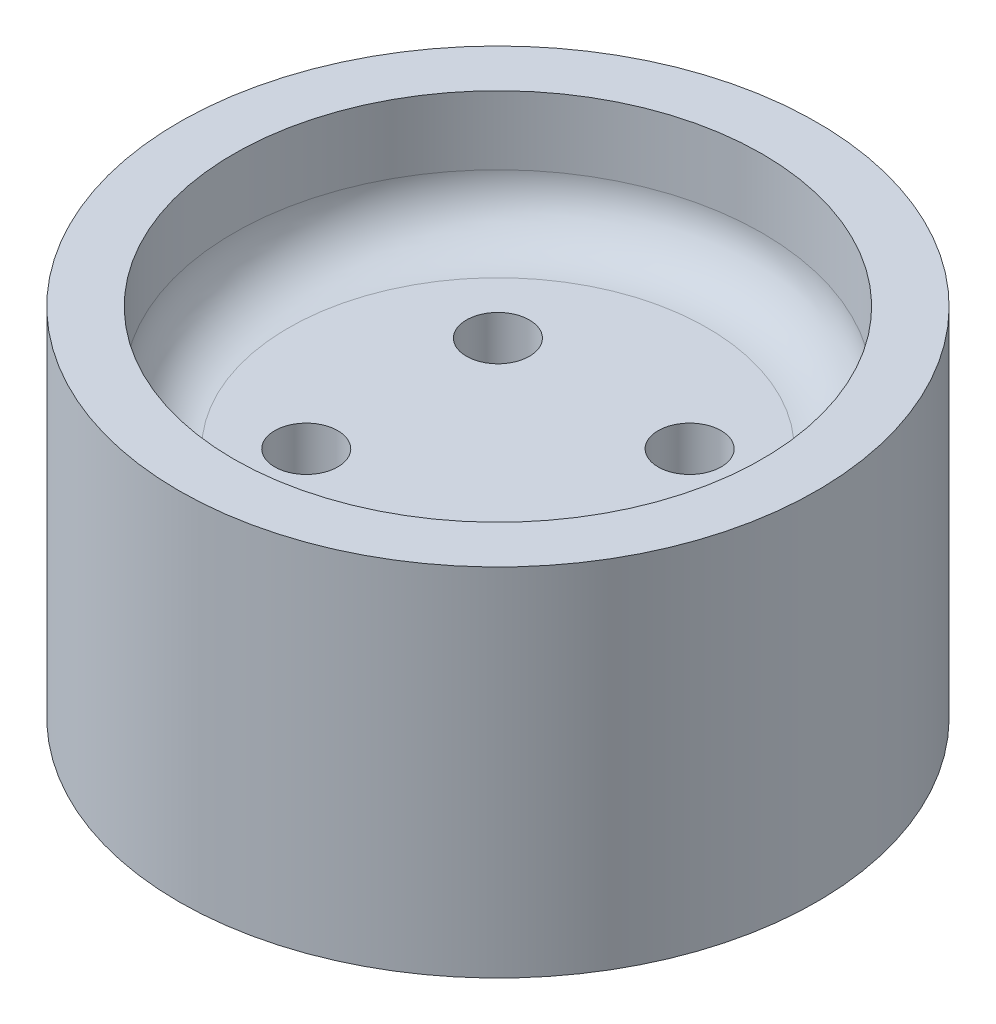
SolidWorks part; units mm, degrees
ref_plane "Front Plane" through (0, 0, 0) normal (0, 0, 1) x (1, 0, 0)
ref_plane "Top Plane" through (0, 0, 0) normal (0, 1, 0) x (1, 0, 0)
ref_plane "Right Plane" through (0, 0, 0) normal (1, 0, 0) x (0, 0, -1)
sketch "Sketch1" plane through (0, 0, 0) normal (0, 1, 0) x (1, 0, 0)
  line L1 (-3.5, 3.5) -> (3.5, 3.5) construction
  line L2 (-3.5, 3.5) -> (-3.5, -3.5) construction
  line L3 (-3.5, -3.5) -> (3.5, -3.5) construction
  line L4 (3.5, 3.5) -> (3.5, -3.5) construction
  line L5 (-3.5, 3.5) -> (3.5, -3.5) construction
  line L6 (-3.5, -3.5) -> (3.5, 3.5) construction
  circle A0 centre (-3.5, 3.5) radius 1.15
  circle A1 centre (3.5, 3.5) radius 1.15
  circle A2 centre (3.5, -3.5) radius 1.15
  circle A3 centre (-3.5, -3.5) radius 1.15
  circle A5 centre (0, 0) radius 11.65
  point P0 (0, 0)
  point P16 (0, 0)
  dimension "D2" = 2.3
  dimension "D1" = 7
  dimension "D3" = 4
extrude "Boss-Extrude1" add sketch "Sketch1" along normal blind 8.5
sketch "Sketch3" plane through (0, 8.5, 0) normal (0, 1, 0) x (1, 0, 0)
  circle A0 centre (0, 0) radius 11.65
  circle A1 centre (0, 0) radius 9.65
  dimension "D1" = 19.3
extrude "Boss-Extrude3" add sketch "Sketch3" along normal blind 4.5
fillet "Fillet2" radius 2 1 edges at (0, 8.5, 9.65)
equation "\"D1@Boss-Extrude3\"=10-5.5"
